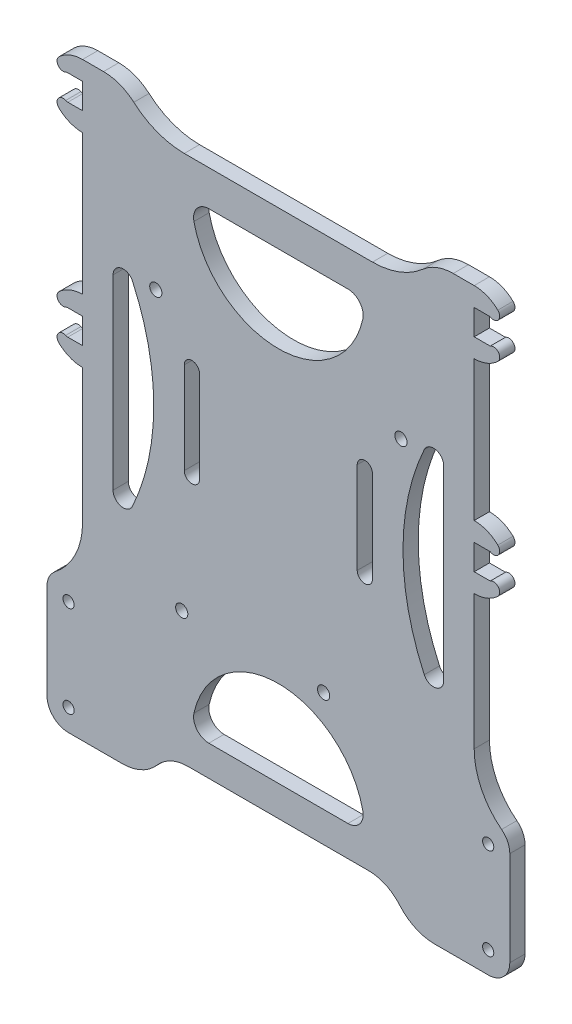
SolidWorks part; units mm, degrees
material "Acrylic (Medium-high impact)"
ref_plane "Front Plane" through (0, 0, 0) normal (0, 0, 1) x (1, 0, 0)
ref_plane "Top Plane" through (0, 0, 0) normal (0, 1, 0) x (1, 0, 0)
ref_plane "Right Plane" through (0, 0, 0) normal (1, 0, 0) x (0, 0, -1)
sketch "Sketch2" plane through (0, 0, 0) normal (0, 0, 1) x (1, 0, 0)
  line L0 (0, 0) -> (0, 25)
  line L1 (0, 25) -> (7, 25)
  line L2 (7, 25) -> (7, 116)
  line L3 (7, 116) -> (15, 116)
  line L4 (15, 116) -> (15, 110)
  line L5 (15, 110) -> (76, 110)
  line L6 (76, 110) -> (76, 116)
  line L7 (76, 116) -> (84, 116)
  line L8 (84, 116) -> (84, 25)
  line L9 (84, 25) -> (91, 25)
  line L10 (91, 25) -> (91, 0)
  line L11 (91, 0) -> (71, 0)
  line L12 (71, 0) -> (71, 6)
  line L13 (71, 6) -> (20, 6)
  line L14 (20, 6) -> (20, 0)
  line L15 (20, 0) -> (0, 0)
  line L16 (45.5, 110) -> (45.5, 6) construction
  line L17 (28.5, 56) -> (28.5, 74) construction
  line L18 (27, 56) -> (27, 74)
  line L19 (30, 56) -> (30, 74)
  line L20 (62.5, 56) -> (62.5, 74) construction
  line L21 (64, 56) -> (64, 74)
  line L22 (61, 56) -> (61, 74)
  circle A0 centre (21.4, 84) radius 1.2
  circle A1 centre (69.6, 82.7) radius 1.2
  circle A2 centre (54.4, 31.9) radius 1.2
  circle A3 centre (26.5, 31.9) radius 1.2
  circle A4 centre (4.25, 22.3) radius 1.1
  circle A5 centre (4.25, 4.3) radius 1.1
  circle A6 centre (86.75, 4.3) radius 1.1
  circle A7 centre (86.75, 22.3) radius 1.1
  circle A8 centre (27.746, -2) radius 8
  circle A9 centre (63.254, -2) radius 8
  circle A10 centre (27, 125) radius 15
  circle A11 centre (64, 125) radius 15
  circle A12 centre (-7, 37.1244) radius 14
  circle A13 centre (98, 37.1244) radius 14
  arc A14 (27, 56) -> (30, 56) centre (28.5, 56) ccw
  arc A15 (30, 74) -> (27, 74) centre (28.5, 74) ccw
  arc A16 (64, 56) -> (61, 56) centre (62.5, 56) cw
  arc A17 (61, 74) -> (64, 74) centre (62.5, 74) cw
  point P49 (28.5, 65)
  point P56 (62.5, 65)
  dimension "D12" = 2.4
  dimension "D13" = 2.4
  dimension "D14" = 2.4
  dimension "D15" = 2.4
  dimension "D26" = 2.2
  dimension "D27" = 2.2
  dimension "D30" = 16
  dimension "D31" = 30
  dimension "D32" = 28
  dimension "D34" = 18
  dimension "D1" = 77
  dimension "D2" = 116
  dimension "D3" = 6
  dimension "D4" = 6
  dimension "D5" = 7
  dimension "D6" = 7
  dimension "D7" = 25
  dimension "D8" = 20
  dimension "D9" = 20
  dimension "D10" = 8
  dimension "D11" = 8
  dimension "D16" = 15.2
  dimension "D17" = 27.9
  dimension "D18" = 5.1
  dimension "D19" = 50.8
  dimension "D20" = 1.3
  dimension "D21" = 24.1
  dimension "D22" = 24.1
  dimension "D23" = 32
  dimension "D24" = 18
  dimension "D25" = 4.25
  dimension "D28" = 4.3
  dimension "D29" = 2.7
  dimension "D33" = 3
  dimension "D35" = 15.5
  dimension "D36" = 45
extrude "Boss-Extrude4" add sketch "Sketch2" along normal blind 3 contours A10 L4 L5 | L6 A11 L5 | L15 L14 L13 L12 L11 L10 L9 L8 L7 L6 L5 L4 L3 L2 L1 L0 A7 A0 A1 A2 A3 A4 A5 A6 A15 L19 A14 L18 L22 A17 L21 A16 | A12 L1 L2 | L9 A13 L8 | L13 A9 L12 | A8 L13 L14
fillet "Fillet2" radius 9 4 edges at (20, 0, 1.5) (71, 0, 1.5) (15, 116, 1.5) (76, 116, 1.5)
fillet "Fillet3" radius 4.2 4 edges at (91, 0, 1.5) (0, 0, 1.5) (0, 25, 1.5) (91, 25, 1.5)
sketch "Sketch3" plane through (0, 0, 3) normal (0, 0, 1) x (1, 0, 0)
  line L0 (45.5, 110) -> (45.5, -49890) construction
  line L1 (27, 110) -> (64, 110) construction
  line L2 (63.254, 6) -> (27.746, 6) construction
  line L3 (28.5, 12) -> (45.5, 12)
  line L4 (45.5, 12) -> (45.5, 29)
  line L5 (28.5, 103) -> (45.5, 103)
  line L6 (45.5, 103) -> (45.5, 86)
  line L7 (7, 37.1244) -> (7, 116) construction
  line L8 (13, 89.923) -> (13, 38.077)
  line L9 (7, 116) -> (11.1255, 116) construction
  arc A0 (45.5, 29) -> (28.5, 12) centre (45.5, 12) ccw
  arc A1 (28.5, 103) -> (45.5, 86) centre (45.5, 103) ccw
  circle A2 centre (-25, 64) radius 46
  point P4 (45.5, 110)
  point P7 (45.5, 6)
  dimension "D1" = 17
  dimension "D4" = 17
  dimension "D5" = 92
  dimension "D2" = 6
  dimension "D3" = 7
  dimension "D6" = 32
  dimension "D7" = 6
  dimension "D8" = 52
extrude "Cut-Extrude1" cut sketch "Sketch3" against normal blind 17 contours L8 A2 | L5 A1 L6 | L4 A0 L3
fillet "Fillet4" radius 3 2 edges at (28.5, 12, 1.5) (28.5, 103, 1.5)
fillet "Fillet5" radius 2 2 edges at (13, 38.077, 1.5) (13, 89.923, 1.5)
sketch "Sketch6" plane through (0, 0, 3) normal (0, 0, 1) x (1, 0, 0)
  line L0 (3.85, 112.2736) -> (7, 112.2736)
  line L1 (7, 37.1244) -> (7, 116) construction
  line L2 (7, 116) -> (11.1255, 116) construction
  line L3 (-8.7855, 109.7736) -> (19.141, 109.7736) construction
  line L4 (7, 112.2736) -> (7, 116)
  line L5 (7, 107.2736) -> (7, 103.5471)
  line L6 (3.85, 107.2736) -> (7, 107.2736)
  line L7 (-6.0681, 89.7736) -> (28.5687, 89.7736) construction
  line L8 (3.85, 72.2736) -> (7, 72.2736)
  line L9 (7, 72.2736) -> (7, 76)
  line L10 (7, 67.2736) -> (7, 63.5471)
  line L11 (3.85, 67.2736) -> (7, 67.2736)
  circle A0 centre (3.1867, 113.2736) radius 1.2
  circle A1 centre (7, 109.2736) radius 6.7264
  circle A2 centre (7, 110.2736) radius 6.7264
  circle A3 centre (3.1867, 106.2736) radius 1.2
  circle A4 centre (3.1867, 73.2736) radius 1.2
  circle A5 centre (7, 69.2736) radius 6.7264
  circle A6 centre (7, 70.2736) radius 6.7264
  circle A7 centre (3.1867, 66.2736) radius 1.2
  dimension "D1" = 2.4
  dimension "D3" = 3.15
  dimension "D2" = 1
  dimension "D4" = 4
  dimension "D5" = 2.5
  dimension "D6" = 20
extrude "Boss-Extrude6" add sketch "Sketch6" against normal up to surface (3 mm away) contours L4 A1 A0 L0 | A0 | A3 | L6 A3 A2 L5 | A4 | L9 A5 A4 L8 | A7 | L11 A7 A6 L10 up to face at (37.1237, 17.7165, 0)
fillet "Fillet6" radius 1 4 edges at (3.85, 107.2736, 1.5) (3.85, 112.2736, 1.5) (3.85, 72.2736, 1.5) (3.85, 67.2736, 1.5)
mirror "Mirror1" about plane through (45.5, 0, -14) normal (-1, 0, 0) of "Boss-Extrude6", "Cut-Extrude1", "Fillet4", "Fillet5"
equation "\"D9@Sketch2\" = \"D8@Sketch2\""
equation "\"D11@Sketch2\"=\"D10@Sketch2\""
equation "\"D13@Sketch2\"=\"D12@Sketch2\""
equation "\"D14@Sketch2\"=\"D12@Sketch2\""
equation "\"D15@Sketch2\"=\"D12@Sketch2\""
equation "\"D27@Sketch2\"=\"D26@Sketch2\""
equation "\"D6@Sketch2\"=\"D5@Sketch2\""
